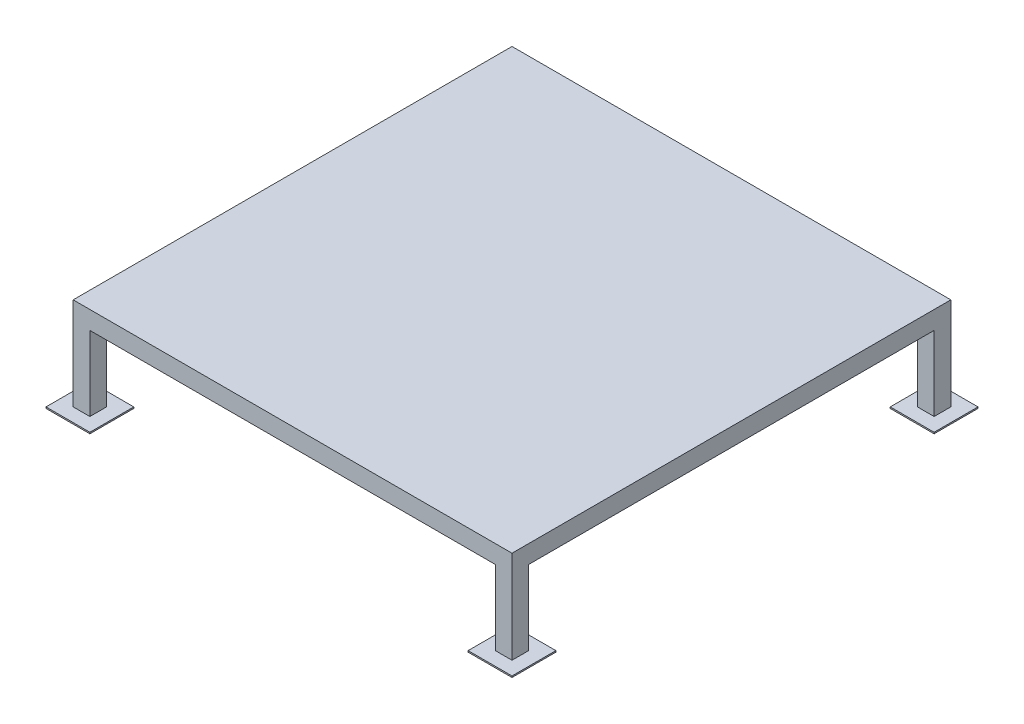
SolidWorks part; units mm, degrees
ref_plane "Alzado" through (0, 0, 0) normal (0, 0, 1) x (1, 0, 0)
ref_plane "Planta" through (0, 0, 0) normal (0, 1, 0) x (1, 0, 0)
ref_plane "Vista lateral" through (0, 0, 0) normal (1, 0, 0) x (0, 0, -1)
sketch "Croquis1" plane through (0, 0, 0) normal (0, 1, 0) x (1, 0, 0)
  line L1 (-500, 500) -> (500, 500)
  line L2 (-500, 500) -> (-500, -500)
  line L3 (-500, -500) -> (500, -500)
  line L4 (500, 500) -> (500, -500)
  line L5 (-500, 500) -> (500, -500) construction
  line L6 (-500, -500) -> (500, 500) construction
  point P0 (0, 0)
  dimension "D1" = 1000
  dimension "D2" = 1000
extrude "Saliente-Extruir1" add sketch "Croquis1" along normal blind 3.175
sketch "Croquis2" plane through (0, 0, 0) normal (0, -1, 0) x (-1, 0, 0)
  line L0 (-500, -500) -> (-500, 500) construction
  line L1 (-500, 500) -> (500, 500) construction
  line L2 (500, 500) -> (500, -500) construction
  line L3 (500, -500) -> (-500, -500) construction
  line L4 (-500, -500) -> (-500, 500)
  line L5 (-500, 500) -> (500, 500)
  line L6 (500, 500) -> (500, -500)
  line L7 (500, -500) -> (-500, -500)
  line L8 (461.9, 461.9) -> (461.9, -461.9)
  line L9 (461.9, -461.9) -> (-461.9, -461.9)
  line L10 (-461.9, -461.9) -> (-461.9, 461.9)
  line L11 (-461.9, 461.9) -> (461.9, 461.9)
  dimension "D1" = 38.1
extrude "Saliente-Extruir2" add sketch "Croquis2" along normal blind 38.1
sketch "Croquis3" plane through (0, -38.1, 0) normal (0, -1, 0) x (1, 0, 0)
  line L0 (500, 500) -> (-500, -500) construction
  line L1 (-500, -500) -> (500, -500) construction
  line L2 (500, -500) -> (-500, 500) construction
  line L3 (500, 500) -> (500, 461.9)
  line L4 (-500, 500) -> (-461.9, 500)
  line L5 (-500, 500) -> (-500, 461.9)
  line L6 (-500, 461.9) -> (-461.9, 461.9)
  line L7 (-461.9, 500) -> (-461.9, 461.9)
  line L8 (500, 461.9) -> (461.9, 461.9)
  line L9 (461.9, 500) -> (461.9, 461.9)
  line L10 (500, 500) -> (461.9, 500)
  line L11 (500, -500) -> (461.9, -500)
  line L12 (461.9, -500) -> (461.9, -461.9)
  line L13 (500, -461.9) -> (461.9, -461.9)
  line L14 (500, -500) -> (500, -461.9)
  line L15 (-500, -500) -> (-500, -461.9)
  line L16 (-500, -461.9) -> (-461.9, -461.9)
  line L17 (-461.9, -500) -> (-461.9, -461.9)
  line L18 (-500, -500) -> (-461.9, -500)
  point P4 (0, 0)
  point P28 (0, 0)
  dimension "D1" = 4
extrude "Saliente-Extruir3" add sketch "Croquis3" along normal blind 170
sketch "Croquis4" plane through (0, -208.1, 0) normal (0, -1, 0) x (1, 0, 0)
  line L0 (-461.9, 500) -> (-500, 461.9) construction
  line L1 (530.95, 430.95) -> (530.95, 530.95)
  line L2 (-430.95, 530.95) -> (-530.95, 530.95)
  line L3 (-430.95, 530.95) -> (-430.95, 430.95)
  line L4 (-430.95, 430.95) -> (-530.95, 430.95)
  line L5 (-530.95, 530.95) -> (-530.95, 430.95)
  line L6 (-430.95, 530.95) -> (-530.95, 430.95) construction
  line L7 (-430.95, 430.95) -> (-530.95, 530.95) construction
  line L8 (530.95, 430.95) -> (430.95, 430.95)
  line L9 (430.95, 430.95) -> (430.95, 530.95)
  line L10 (530.95, 530.95) -> (430.95, 530.95)
  line L11 (430.95, -530.95) -> (530.95, -530.95)
  line L12 (430.95, -530.95) -> (430.95, -430.95)
  line L13 (430.95, -430.95) -> (530.95, -430.95)
  line L14 (530.95, -530.95) -> (530.95, -430.95)
  line L15 (-530.95, -430.95) -> (-530.95, -530.95)
  line L16 (-530.95, -430.95) -> (-430.95, -430.95)
  line L17 (-430.95, -430.95) -> (-430.95, -530.95)
  line L18 (-530.95, -530.95) -> (-430.95, -530.95)
  point P4 (-480.95, 480.95)
  point P9 (0, 0)
  point P26 (0, 0)
  dimension "D1" = 100
  dimension "D2" = 100
  dimension "D3" = 4
extrude "Saliente-Extruir4" add sketch "Croquis4" along normal blind 3.175
